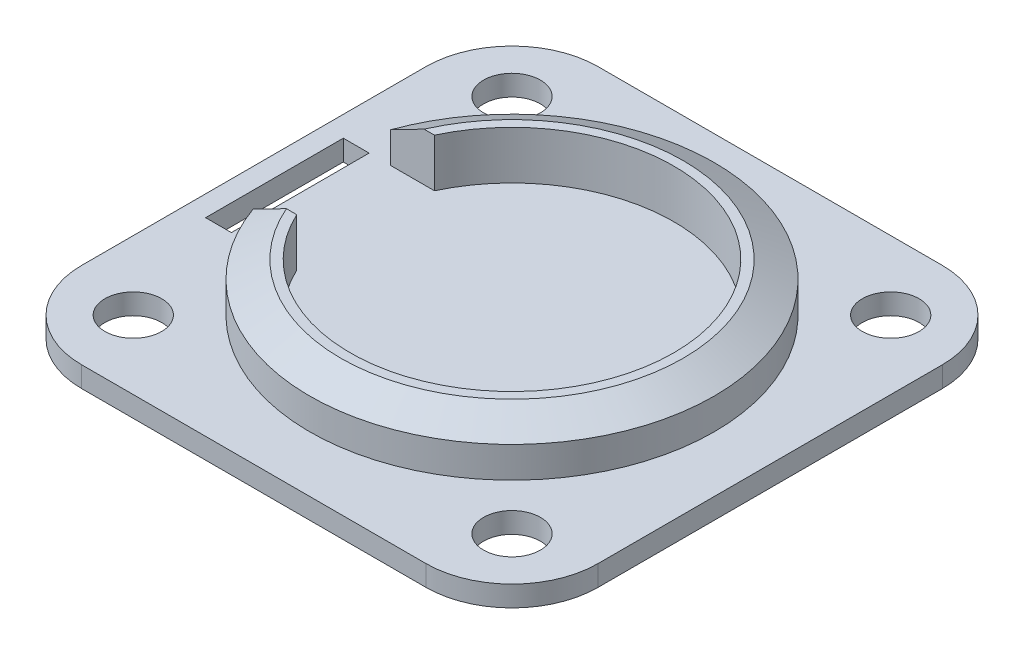
SolidWorks part; units mm, degrees
ref_plane "Front Plane" through (0, 0, 0) normal (0, 0, 1) x (1, 0, 0)
ref_plane "Top Plane" through (0, 0, 0) normal (0, 1, 0) x (1, 0, 0)
ref_plane "Right Plane" through (0, 0, 0) normal (1, 0, 0) x (0, 0, -1)
sketch "Sketch2" plane through (0, 0, 0) normal (0, 1, 0) x (1, 0, 0)
  circle A0 centre (0, 0) radius 11.75
  dimension "D1" = 23.5
extrude "Boss-Extrude1" add sketch "Sketch2" along normal blind 4
sketch "Sketch3" plane through (0, 4, 0) normal (0, 1, 0) x (1, 0, 0)
  line L0 (-8.5065, 4) -> (-15.4735, 4)
  line L1 (-15.4735, 4) -> (-15.4735, -4)
  line L2 (-15.4735, -4) -> (-8.5065, -4)
  arc A0 (-8.5065, -4) -> (-8.5065, 4) centre (0, 0) ccw
  dimension "D1" = 18.8
  dimension "D2" = 4
  dimension "D3" = 8
extrude "Cut-Extrude1" cut sketch "Sketch3" against normal blind 4
sketch "Sketch4" plane through (0, 0, 0) normal (0, 1, 0) x (1, 0, 0)
  line L16 (-15, 15) -> (15, 15)
  line L17 (-15, 15) -> (-15, -15)
  line L18 (-15, -15) -> (15, -15)
  line L19 (15, 15) -> (15, -15)
  line L20 (-15, 15) -> (15, -15) construction
  line L21 (-15, -15) -> (15, 15) construction
  circle A7 centre (11, -11) radius 1.65
  circle A9 centre (-11, -11) radius 1.65
  circle A11 centre (-11, 11) radius 1.65
  circle A13 centre (11, 11) radius 1.65
  point P1 (0, 0)
  point P13 (0, 0)
  point P33 (0, 0)
  dimension "D1" = 11
  dimension "D2" = 15
  dimension "D5" = 3.3
  dimension "D3" = 11
  dimension "D4" = 4
extrude "Boss-Extrude2" add sketch "Sketch4" along normal blind 1.2
fillet "Fillet2" radius 5 4 edges at (15, 0.6, -15) (15, 0.6, 15) (-15, 0.6, 15) (-15, 0.6, -15)
sketch "Sketch6" plane through (0, 0, 0) normal (0, 1, 0) x (1, 0, 0)
  line L0 (-15, 10) -> (-15, -10) construction
  line L1 (-13.8, 4) -> (-12.3, 4)
  line L2 (-13.8, 4) -> (-13.8, -4)
  line L3 (-13.8, -4) -> (-12.3, -4)
  line L4 (-12.3, 4) -> (-12.3, -4)
  line L5 (-13.8, 4) -> (-12.3, -4) construction
  line L6 (-13.8, -4) -> (-12.3, 4) construction
  point P0 (-13.05, 0)
  dimension "D1" = 8
  dimension "D2" = 1.5
  dimension "D3" = 1.2
extrude "Cut-Extrude2" cut sketch "Sketch6" along normal blind 10
chamfer "Chamfer1" distance 1 angle 61 1 edges at (11.75, 4, 0)
